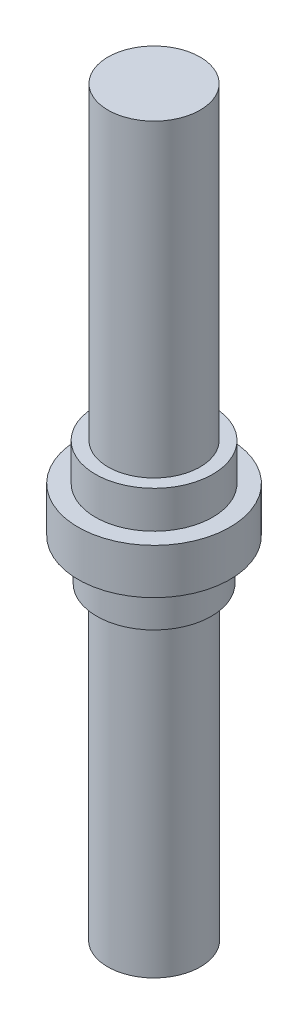
SolidWorks part; units mm, degrees
ref_plane "前视基准面" through (0, 0, 0) normal (0, 0, 1) x (1, 0, 0)
ref_plane "上视基准面" through (0, 0, 0) normal (0, 1, 0) x (1, 0, 0)
ref_plane "右视基准面" through (0, 0, 0) normal (1, 0, 0) x (0, 0, -1)
sketch "草图2" plane through (0, 0, 0) normal (1, 0, 0) x (0, 0, -1)
  line L0 (0, 0) -> (0, 21.9196) construction
  line L2 (0, 10) -> (1.5, 10)
  line L3 (0, 10) -> (0, 0)
  line L4 (0, 0) -> (1.5, 0)
  line L5 (1.5, 10) -> (1.5, 0)
  line L6 (0, 11.3332) -> (1.852, 11.3332)
  line L7 (0, 11.3332) -> (0, 10)
  line L8 (0, 10) -> (1.852, 10)
  line L9 (1.852, 11.3332) -> (1.852, 10)
  line L10 (0, 12.7991) -> (2.4569, 12.7991)
  line L11 (0, 12.7991) -> (0, 11.3332)
  line L12 (0, 11.3332) -> (2.4569, 11.3332)
  line L13 (2.4569, 12.7991) -> (2.4569, 11.3332)
  line L14 (0, 14.0027) -> (1.8981, 14.0027)
  line L15 (0, 14.0027) -> (0, 12.7991)
  line L16 (0, 12.7991) -> (1.8981, 12.7991)
  line L17 (1.8981, 14.0027) -> (1.8981, 12.7991)
  line L18 (1.4897, 14.0027) -> (0, 14.0027)
  line L19 (1.4897, 14.0027) -> (1.4897, 24.0027)
  line L20 (1.4897, 24.0027) -> (0, 24.0027)
  line L21 (0, 14.0027) -> (0, 24.0027)
  point P18 (2.4569, 12.7991)
  point P19 (1.8981, 14.0027)
  point P20 (1.4897, 18.9247)
  dimension "D1" = 1.5
  dimension "D2" = 10
  dimension "D3" = 10
revolve "旋转1" add sketch "草图2" angle 360 about L0
